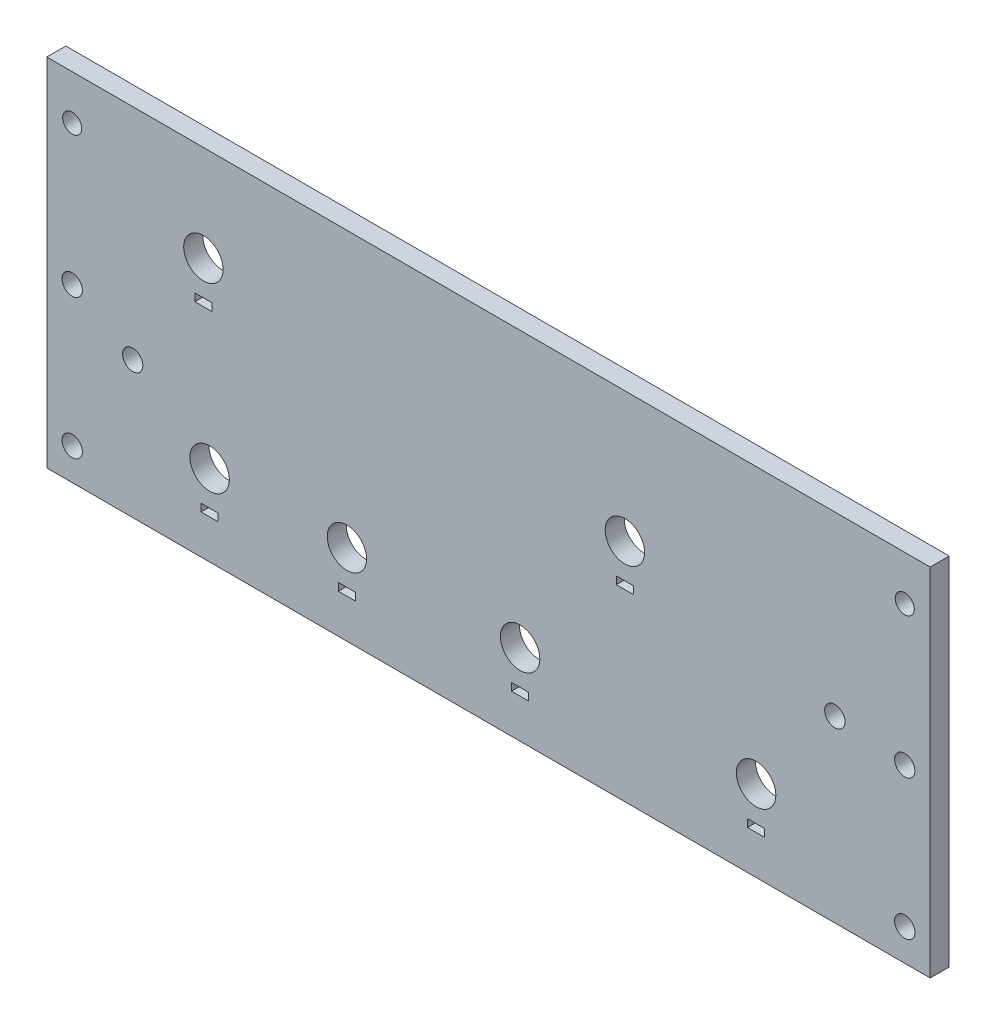
SolidWorks part; units mm, degrees
ref_plane "Front Plane" through (0, 0, 0) normal (0, 0, 1) x (1, 0, 0)
ref_plane "Top Plane" through (0, 0, 0) normal (0, 1, 0) x (1, 0, 0)
ref_plane "Right Plane" through (0, 0, 0) normal (1, 0, 0) x (0, 0, -1)
sketch "Sketch1" plane through (0, 0, 0) normal (0, 0, 1) x (1, 0, 0)
  line L1 (0, 0) -> (139, 0)
  line L2 (0, 0) -> (0, 56)
  line L3 (0, 56) -> (139, 56)
  line L4 (139, 0) -> (139, 56)
  line L5 (69.5, 56) -> (69.5, 0) construction
  line L6 (24.6456, 40.9066) -> (24.6456, 34.9066) construction
  line L7 (23.2956, 34.3066) -> (25.9956, 34.3066)
  line L8 (23.2956, 34.3066) -> (23.2956, 35.5066)
  line L9 (23.2956, 35.5066) -> (25.9956, 35.5066)
  line L10 (25.9956, 34.3066) -> (25.9956, 35.5066)
  line L11 (23.2956, 34.3066) -> (25.9956, 35.5066) construction
  line L12 (23.2956, 35.5066) -> (25.9956, 34.3066) construction
  line L13 (25.6233, 12.7439) -> (25.6233, 6.7439) construction
  line L14 (24.2733, 6.1439) -> (26.9733, 6.1439)
  line L15 (24.2733, 6.1439) -> (24.2733, 7.3439)
  line L16 (24.2733, 7.3439) -> (26.9733, 7.3439)
  line L17 (26.9733, 6.1439) -> (26.9733, 7.3439)
  line L18 (24.2733, 6.1439) -> (26.9733, 7.3439) construction
  line L19 (24.2733, 7.3439) -> (26.9733, 6.1439) construction
  line L20 (111.6129, 12.7439) -> (111.6129, 6.7439) construction
  line L21 (110.2629, 6.1439) -> (112.9629, 6.1439)
  line L22 (110.2629, 6.1439) -> (110.2629, 7.3439)
  line L23 (110.2629, 7.3439) -> (112.9629, 7.3439)
  line L24 (112.9629, 6.1439) -> (112.9629, 7.3439)
  line L25 (110.2629, 6.1439) -> (112.9629, 7.3439) construction
  line L26 (110.2629, 7.3439) -> (112.9629, 6.1439) construction
  line L27 (90.9664, 35.5) -> (90.9664, 29.5) construction
  line L28 (89.6164, 28.9) -> (92.3164, 28.9)
  line L29 (89.6164, 28.9) -> (89.6164, 30.1)
  line L30 (89.6164, 30.1) -> (92.3164, 30.1)
  line L31 (92.3164, 28.9) -> (92.3164, 30.1)
  line L32 (89.6164, 28.9) -> (92.3164, 30.1) construction
  line L33 (89.6164, 30.1) -> (92.3164, 28.9) construction
  line L34 (74.4802, 12.7439) -> (74.4802, 6.7439) construction
  line L35 (73.1302, 6.1439) -> (75.8302, 6.1439)
  line L36 (73.1302, 6.1439) -> (73.1302, 7.3439)
  line L37 (73.1302, 7.3439) -> (75.8302, 7.3439)
  line L38 (75.8302, 6.1439) -> (75.8302, 7.3439)
  line L39 (73.1302, 6.1439) -> (75.8302, 7.3439) construction
  line L40 (73.1302, 7.3439) -> (75.8302, 6.1439) construction
  line L41 (47.23, 12.7439) -> (47.23, 6.7439) construction
  line L42 (45.88, 6.1439) -> (48.58, 6.1439)
  line L43 (45.88, 6.1439) -> (45.88, 7.3439)
  line L44 (45.88, 7.3439) -> (48.58, 7.3439)
  line L45 (48.58, 6.1439) -> (48.58, 7.3439)
  line L46 (45.88, 6.1439) -> (48.58, 7.3439) construction
  line L47 (45.88, 7.3439) -> (48.58, 6.1439) construction
  circle A4 centre (4, 27) radius 1.6
  circle A5 centre (135, 27) radius 1.6
  circle A6 centre (135, 5) radius 1.6
  circle A7 centre (4, 5) radius 1.6
  circle A9 centre (13.5185, 21.5) radius 1.6
  circle A11 centre (124, 28.1942) radius 1.6
  circle A12 centre (24.6456, 40.9066) radius 3.1
  circle A13 centre (25.6233, 12.7439) radius 3.1
  circle A14 centre (111.6129, 12.7439) radius 3.1
  circle A15 centre (90.9664, 35.5) radius 3.1
  circle A16 centre (74.4802, 12.7439) radius 3.1
  circle A17 centre (47.23, 12.7439) radius 3.1
  circle A18 centre (4, 49) radius 1.5 construction
  circle A19 centre (4, 49) radius 1.5
  circle A20 centre (135, 49) radius 1.5 construction
  circle A21 centre (135, 49) radius 1.5
  point P7 (24.6456, 34.9066)
  point P8 (0, 28)
  point P20 (25.6233, 6.7439)
  point P40 (111.6129, 6.7439)
  point P49 (90.9664, 29.5)
  point P59 (74.4802, 6.7439)
  point P69 (47.23, 6.7439)
  dimension "D3" = 1.2
  dimension "D4" = 6
  dimension "D5" = 1.2
  dimension "D8" = 3.2
  dimension "D24" = 1.2
  dimension "D25" = 21.5
  dimension "D29" = 9.1
  dimension "D19" = 3.2
  dimension "D6" = 9.1
  dimension "D16" = 6.2
  dimension "D21" = 1.2
  dimension "D23" = 6.2
  dimension "D7" = 6.2
  dimension "D27" = 6.2
  dimension "D30" = 6.2
  dimension "D1" = 139
  dimension "D2" = 56
  dimension "D11" = 1.2
  dimension "D12" = 4
  dimension "D13" = 5
  dimension "D14" = 22
  dimension "D15" = 9.1
  dimension "D17" = 15
  dimension "D18" = 15
  dimension "D20" = 4
  dimension "D22" = 9.1
  dimension "D26" = 9.1
  dimension "D28" = 1.2
  dimension "D9" = 2
  dimension "D10" = 2
extrude "Boss-Extrude1" add sketch "Sketch1" along normal blind 3
